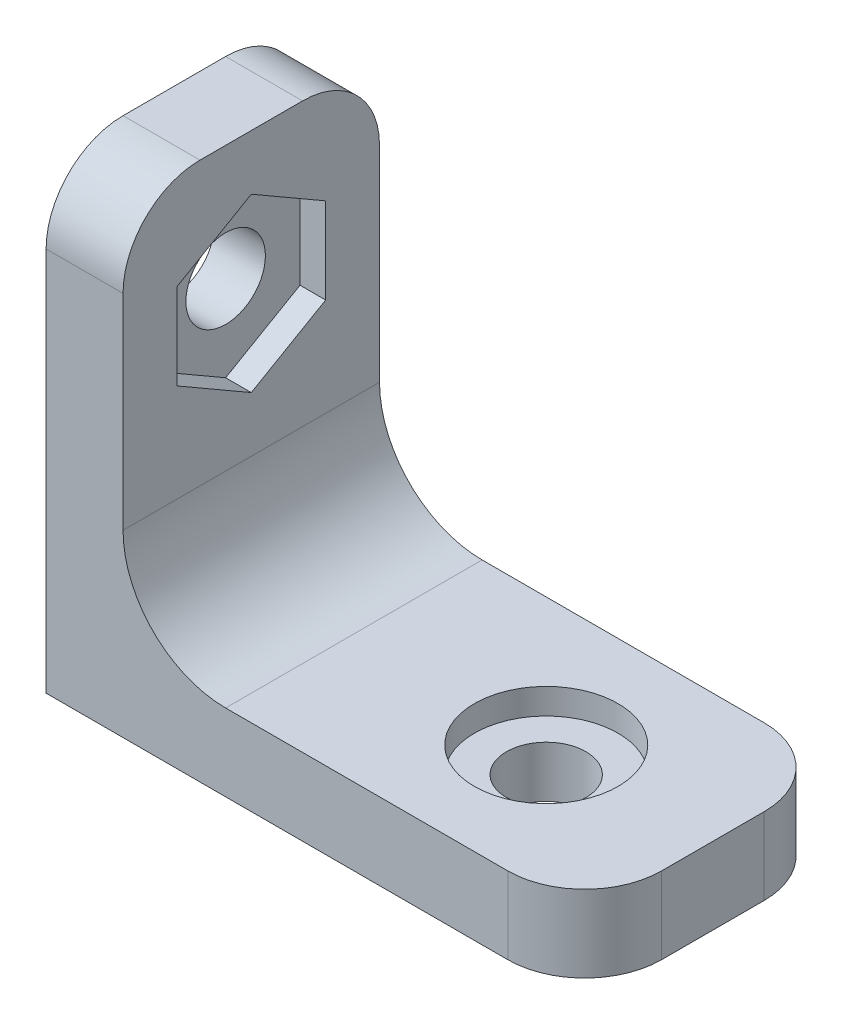
SolidWorks part; units mm, degrees
ref_plane "Alzado" through (0, 0, 0) normal (0, 0, 1) x (1, 0, 0)
ref_plane "Planta" through (0, 0, 0) normal (0, 1, 0) x (1, 0, 0)
ref_plane "Vista lateral" through (0, 0, 0) normal (1, 0, 0) x (0, 0, -1)
sketch "Croquis1" plane through (0, 0, 0) normal (0, 1, 0) x (1, 0, 0)
  line L1 (0, 0) -> (21, 0)
  line L2 (0, 0) -> (0, 10)
  line L3 (0, 10) -> (21, 10)
  line L4 (21, 0) -> (21, 10)
  circle A0 centre (14.5, 5) radius 1.55
  dimension "D3" = 3.1
  dimension "D1" = 21
  dimension "D2" = 10
  dimension "D4" = 14.5
  dimension "D5" = 5
extrude "Saliente-Extruir1" add sketch "Croquis1" along normal blind 3
sketch "Croquis2" plane through (0, 3, 0) normal (0, 1, 0) x (1, 0, 0)
  line L0 (0, 0) -> (21, 0) construction
  line L1 (0, 10) -> (3, 10)
  line L2 (0, 10) -> (0, 0)
  line L3 (0, 0) -> (3, 0)
  line L4 (3, 10) -> (3, 0)
  dimension "D1" = 3
extrude "Saliente-Extruir2" add sketch "Croquis2" along normal blind 15
sketch "Croquis3" plane through (0, 0, 0) normal (-1, 0, 0) x (0, 0, 1)
  line L0 (-10, 0) -> (0, 0) construction
  line L1 (0, 18) -> (0, 0) construction
  circle A0 centre (-5, 12.5) radius 1.55
  dimension "D1" = 3.1
  dimension "D2" = 12.5
  dimension "D3" = 5
extrude "Cortar-Extruir1" cut sketch "Croquis3" against normal up to surface (3 mm away) up to face at (3, 10.5, -5)
sketch "Croquis4" plane through (0, 3, 0) normal (0, 1, 0) x (1, 0, 0)
  circle A0 centre (14.5, 5) radius 2.8
  dimension "D1" = 5.6
extrude "Cortar-Extruir2" cut sketch "Croquis4" against normal blind 1
sketch "Croquis5" plane through (3, 0, 0) normal (1, 0, 0) x (0, 0, -1)
  line L1 (7.9, 14.1743) -> (5, 15.8486)
  line L2 (5, 15.8486) -> (2.1, 14.1743)
  line L3 (2.1, 14.1743) -> (2.1, 10.8257)
  line L4 (2.1, 10.8257) -> (5, 9.1514)
  line L5 (5, 9.1514) -> (7.9, 10.8257)
  line L6 (7.9, 10.8257) -> (7.9, 14.1743)
  line L8 (10, 18) -> (10, 3) construction
  circle A0 centre (5, 12.5) radius 2.9 construction
  dimension "D1" = 5.8
extrude "Cortar-Extruir3" cut sketch "Croquis5" against normal blind 1
fillet "Redondeo1" radius 3 4 edges at (1.5, 18, -10) (1.5, 18, 0) (21, 1.5, 0) (21, 1.5, -10)
fillet "Redondeo2" radius 4 1 edges at (3, 3, -5)
